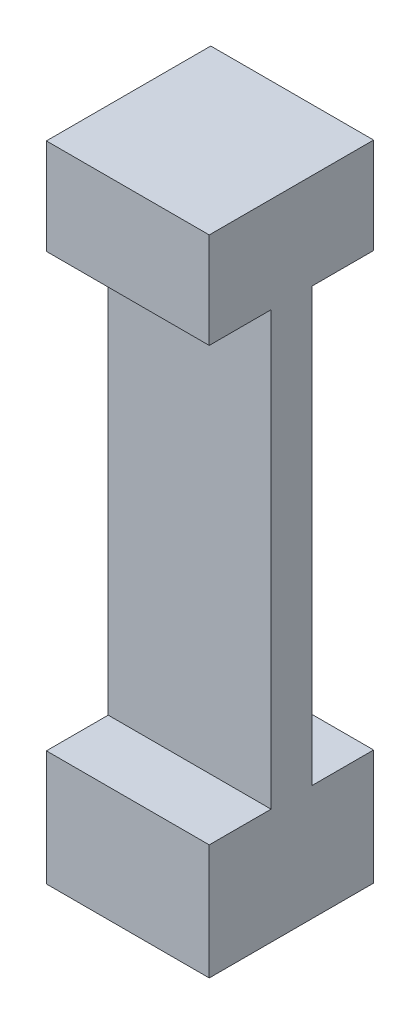
SolidWorks part; units mm, degrees
ref_plane "Front Plane" through (0, 0, 0) normal (0, 0, 1) x (1, 0, 0)
ref_plane "Top Plane" through (0, 0, 0) normal (0, 1, 0) x (1, 0, 0)
ref_plane "Right Plane" through (0, 0, 0) normal (1, 0, 0) x (0, 0, -1)
sketch "Sketch1" plane through (0, 0, 0) normal (0, 1, 0) x (1, 0, 0)
  line L1 (-31.5681, -40.3791) -> (48.4, -40.3791)
  line L2 (-31.5681, -40.3791) -> (-31.5681, 40.3257)
  line L3 (-31.5681, 40.3257) -> (48.4, 40.3257)
  line L4 (48.4, -40.3791) -> (48.4, 40.3257)
  line L5 (-31.5681, -40.3791) -> (48.4, 40.3257) construction
  line L6 (-31.5681, 40.3257) -> (48.4, -40.3791) construction
  point P0 (8.416, -0.0267)
extrude "Boss-Extrude1" add sketch "Sketch1" along normal up to surface (299.3699 mm away)
sketch "Sketch2" plane through (48.4, 0, 0) normal (1, 0, 0) x (0, 0, -1)
  line L1 (-40.3791, 292.3736) -> (-40.3791, 0) construction
  line L3 (-10.0267, 40) -> (-40.3791, 40)
  line L4 (-10.0267, 40) -> (-10.0267, 260)
  line L5 (-0.0267, 0) -> (-0.0267, 292.3736) construction
  line L6 (-40.3791, 0) -> (40.3257, 0) construction
  line L7 (-40.3791, 292.3736) -> (40.3257, 292.3736) construction
  line L8 (9.9733, 40) -> (40.3257, 40)
  line L9 (40.3257, 252.3736) -> (9.9733, 252.3736)
  line L10 (9.9733, 252.3736) -> (9.9733, 40)
  line L12 (40.3257, 252.3736) -> (40.3257, 40)
  line L13 (-10.0267, 260) -> (-40.3791, 260)
  line M2 (40.3257, 0) -> (40.3257, 292.3736)
  line M4 (-40.3791, 292.3736) -> (-40.3791, 0)
  dimension "D2" = 40
sketch "Sketch4" plane through (0, 0, 0) normal (0, -1, 0) x (-1, 0, 0)
  line L3 (-8.416, -0.0267) -> (-8.416, 40.3257) construction
  line L5 (-48.4, 40.3257) -> (31.5681, 40.3257) construction
extrude "Cut-Extrude1" cut sketch "Sketch2" against normal through all both and the other way through all contours L4 L13 L3 M4 | L9 L10 L8 M2
sketch "Sketch5" plane through (0, 260, 0) normal (0, -1, 0) x (1, 0, 0)
  line L4 (48.4, 40.3791) -> (-31.5681, 40.3791)
  line L5 (-31.5681, 40.3791) -> (-31.5681, 10.0267)
  line L6 (-31.5681, 10.0267) -> (48.4, 10.0267)
  line L7 (48.4, 10.0267) -> (48.4, 40.3791)
  line L8 (48.4, 40.3791) -> (-31.5681, 40.3791)
  line L9 (-31.5681, 40.3791) -> (-31.5681, 10.0267)
  line L10 (-31.5681, 10.0267) -> (48.4, 10.0267)
  line L11 (48.4, 10.0267) -> (48.4, 40.3791)
  dimension "D1" = 0
extrude "Boss-Extrude2" add sketch "Sketch5" along normal up to surface (7.6264 mm away)
sketch "Sketch6" plane through (25.7527, 294.355, 0) normal (0.0872, 0.9962, 0) x (0.9962, -0.0872, 0)
  line L4 (22.7338, 40.3257) -> (-57.5397, 40.3257)
  line L5 (-57.5397, 40.3257) -> (-57.5397, -40.3791)
  line L6 (-57.5397, -40.3791) -> (22.7338, -40.3791)
  line L7 (22.7338, -40.3791) -> (22.7338, 40.3257)
  line L8 (22.7338, 40.3257) -> (-57.5397, 40.3257)
  line L9 (-57.5397, 40.3257) -> (-57.5397, -40.3791)
  line L10 (-57.5397, -40.3791) -> (22.7338, -40.3791)
  line L11 (22.7338, -40.3791) -> (22.7338, 40.3257)
  dimension "D1" = 0
sketch "Sketch7" plane through (0, 0, 40.3791) normal (0, 0, 1) x (1, 0, 0)
  line L0 (-31.5681, 299.3699) -> (48.4, 299.3699)
  line L1 (48.4, 299.3699) -> (48.4, 292.3736)
  line L2 (48.4, 292.3736) -> (-31.5681, 299.3699) construction
  line L3 (48.4, 292.3736) -> (-31.5681, 299.3699)
  line L4 (48.4, 292.3736) -> (48.4, 252.3736) construction
extrude "Boss-Extrude3" add sketch "Sketch7" against normal up to surface (80.7048 mm away)
sketch "Sketch8" plane through (0, 299.3699, 0) normal (0, 1, 0) x (1, 0, 0)
  line L0 (8.416, 40.3257) -> (8.416, -0.0134) construction
  line L1 (-31.5681, 40.3257) -> (48.4, 40.3257) construction
  line L3 (-31.5681, 0) -> (8.416, -0.0134) construction
  line L4 (-31.5681, -40.3791) -> (-31.5681, 40.3257) construction
sketch "Sketch9" plane through (0, 0, 0) normal (0, -1, 0) x (1, 0, 0)
  line L4 (48.4, -40.3257) -> (48.4, 40.3791)
  line L5 (48.4, 40.3791) -> (-31.5681, 40.3791)
  line L6 (-31.5681, 40.3791) -> (-31.5681, -40.3257)
  line L7 (-31.5681, -40.3257) -> (48.4, -40.3257)
  line L8 (48.4, -40.3257) -> (48.4, 40.3791)
  line L9 (48.4, 40.3791) -> (-31.5681, 40.3791)
  line L10 (-31.5681, 40.3791) -> (-31.5681, -40.3257)
  line L11 (-31.5681, -40.3257) -> (48.4, -40.3257)
  dimension "D1" = 0
extrude "Boss-Extrude4" add sketch "Sketch9" along normal up to surface (16.6201 mm away)
